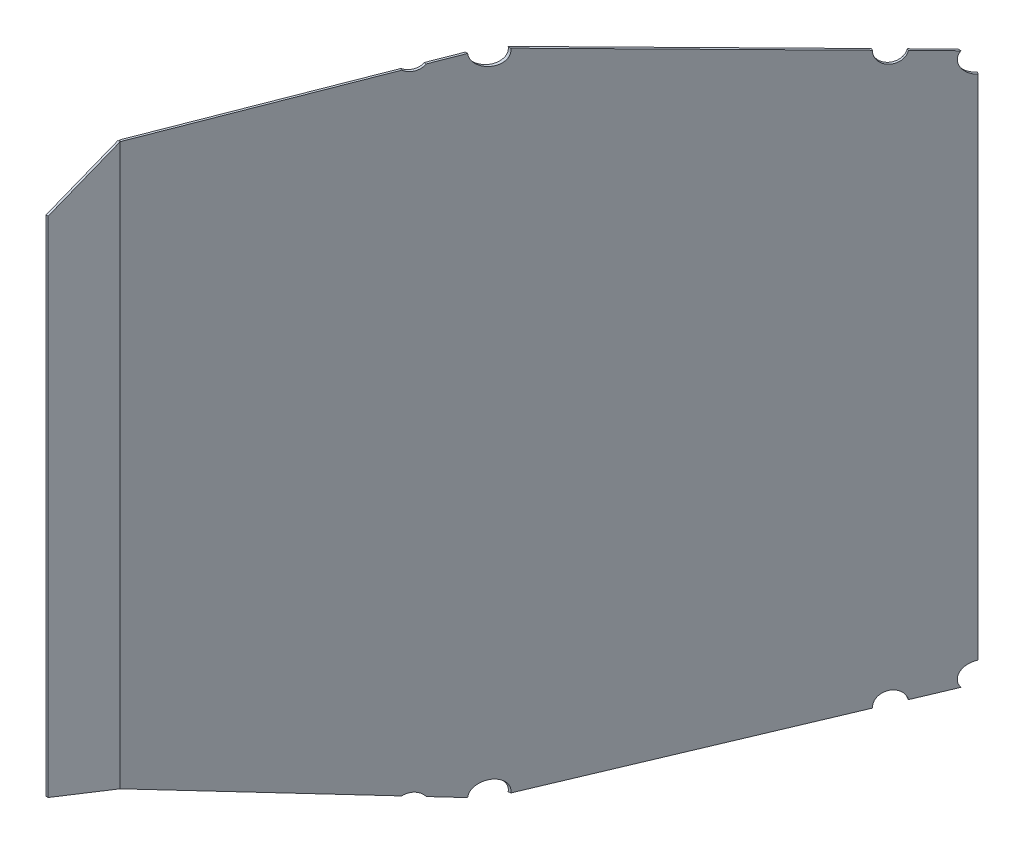
SolidWorks part; units mm, degrees
material "6061-T6 (SS)"
ref_plane "X-Y Datum" through (0, 0, 0) normal (0, 0, 1) x (1, 0, 0)
ref_plane "X-Z Datum" through (0, 0, 0) normal (0, 1, 0) x (1, 0, 0)
ref_plane "Y-Z Datum" through (0, 0, 0) normal (1, 0, 0) x (0, 0, -1)
ref_plane "Plane2" through (251.4767, 0, 168.3074) normal (-0.831, 0, -0.5562) x (-0.5562, 0, 0.831)
sketch "Sketch3" plane through (251.4767, 0, 168.3074) normal (-0.831, 0, -0.5562) x (-0.5562, 0, 0.831)
  line L0 (-187.2045, -273.05) -> (-187.2045, 273.05)
  line L1 (-187.2045, 273.05) -> (164.4025, 323.85)
  line L2 (429.2995, -279.4) -> (429.2995, 279.4)
  line L3 (429.2995, 279.4) -> (164.4025, 323.85)
  line L4 (-187.2045, 0) -> (429.2995, 0)
  line L5 (429.2995, -279.4) -> (164.4025, -323.85)
  line L6 (-187.2045, -273.05) -> (164.4025, -323.85)
  point P9 (164.4025, 323.85)
  dimension "D1" = 273.05
  dimension "D2" = 279.4
  dimension "D3" = 323.85
extrude "Boss-Extrude1" add sketch "Sketch3" along normal blind 2.159 contours L0 L4 L2 L3 L1 | L0 L6 L5 L2 L4
ref_plane "Plane3" through (12.7, 0, 0) normal (-1, 0, 0) x (0, 0, 1)
sketch "Sketch4" plane through (12.7, 0, 0) normal (-1, 0, 0) x (0, 0, 1)
  line L0 (525.0759, -279.4) -> (525.0759, 279.4) construction
  line L1 (525.0759, -279.4) -> (525.0759, 279.4)
  line L3 (525.0759, 0) -> (596.9, 0)
  line L4 (525.0759, 279.4) -> (596.9, 251.0123)
  line L5 (596.9, 251.0123) -> (596.9, -251.0123)
  line L6 (525.0759, -279.4) -> (596.9, -251.0123)
extrude "Boss-Extrude2" add sketch "Sketch4" along normal blind 2.159 separate body contours L1 L6 L5 L3 | L5 L4 L1 L3
ref_plane "Plane4" through (825.5, 177.8, 47.625) normal (-0.9802, 0.1844, -0.0728) x (-0.0715, 0.0135, 0.9973)
sketch "Sketch5" plane through (825.5, 177.8, 47.625) normal (-0.9802, 0.1844, -0.0728) x (-0.0715, 0.0135, 0.9973)
  circle A0 centre (0, 0) radius 12.954
  dimension "D1" = 25.908
extrude "Cut-Extrude1" cut sketch "Sketch5" along normal blind 621.665
ref_plane "Plane5" through (825.5, 227.0125, 304.8) normal (-0.8987, 0.1001, -0.4271) x (-0.4245, 0.0473, 0.9042)
sketch "Sketch6" plane through (825.5, 227.0125, 304.8) normal (-0.8987, 0.1001, -0.4271) x (-0.4245, 0.0473, 0.9042)
  circle A0 centre (0, 0) radius 12.954
  dimension "D1" = 25.908
extrude "Cut-Extrude2" cut sketch "Sketch6" along normal through all
ref_plane "Plane6" through (825.5, 227.0125, 304.8) normal (-0.9902, 0.1398, -0.0002) x (-0.0002, 0, 1)
sketch "Sketch7" plane through (825.5, 227.0125, 304.8) normal (-0.9902, 0.1398, -0.0002) x (-0.0002, 0, 1)
  circle A0 centre (0, 0) radius 12.954
  dimension "D1" = 25.908
extrude "Cut-Extrude3" cut sketch "Sketch7" along normal through all
ref_plane "Plane7" through (825.5, 220.2924, 603.4647) normal (-0.9311, 0.1391, -0.3371) x (-0.3334, 0.0498, 0.9415)
sketch "Sketch8" plane through (825.5, 220.2924, 603.4647) normal (-0.9311, 0.1391, -0.3371) x (-0.3334, 0.0498, 0.9415)
  circle A0 centre (0, 0) radius 12.954
  dimension "D1" = 25.908
extrude "Cut-Extrude4" cut sketch "Sketch8" along normal through all
mirror "Mirror1" about plane through (0, 0, 0) normal (0, 1, 0) of "Cut-Extrude4", "Cut-Extrude3", "Cut-Extrude2", "Cut-Extrude1"
